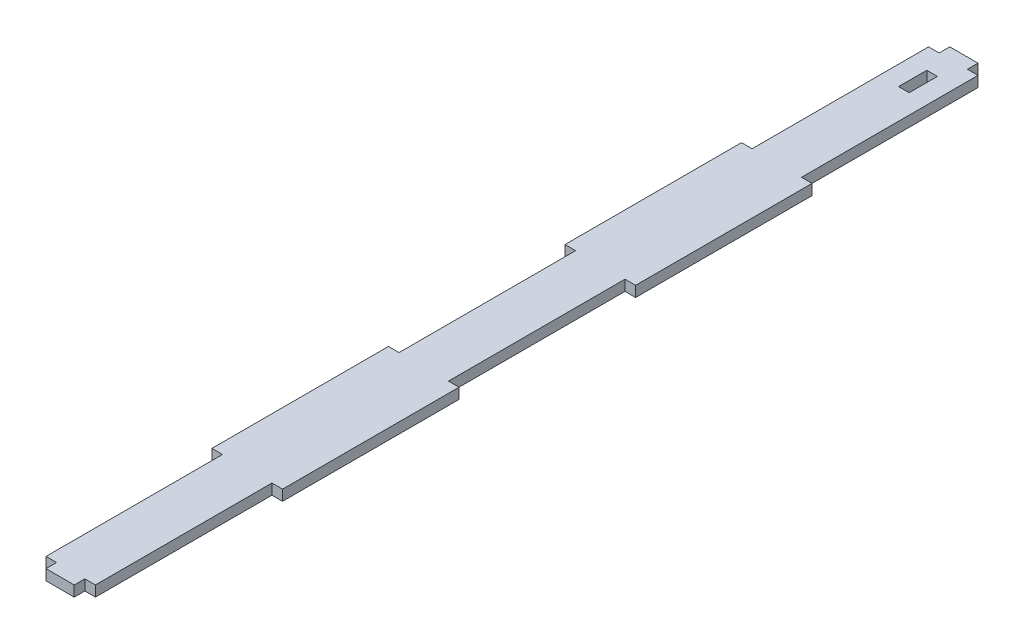
SolidWorks part; units mm, degrees
ref_plane "Alzado" through (0, 0, 0) normal (0, 0, 1) x (1, 0, 0)
ref_plane "Planta" through (0, 0, 0) normal (0, 1, 0) x (1, 0, 0)
ref_plane "Vista lateral" through (0, 0, 0) normal (1, 0, 0) x (0, 0, -1)
sketch "Croquis1" plane through (0, 0, 0) normal (0, 1, 0) x (1, 0, 0)
  line L0 (10, 253.1162) -> (14, 253.1162)
  line L1 (20, 50.1162) -> (20, 100.1162)
  line L2 (3, 200.1162) -> (0, 200.1162)
  line L3 (17, 250.1162) -> (17, 200.1162)
  line L4 (3, 100.1162) -> (3, 150.1162)
  line L5 (20, 150.1162) -> (17, 150.1162)
  line L6 (20, 150.1162) -> (20, 200.1162)
  line L7 (17, 200.1162) -> (20, 200.1162)
  line L8 (0, 200.1162) -> (0, 150.1162)
  line L9 (0, 100.1162) -> (0, 50.1162)
  line L10 (17, 250.1162) -> (14, 250.1162)
  line L12 (17, 150.1162) -> (17, 100.1162)
  line L13 (3, 150.1162) -> (3, 100.1162)
  line L14 (17, 50.1162) -> (20, 50.1162)
  line L15 (10, 253.1162) -> (10, 240.1162) construction
  line L16 (20, 100.1162) -> (17, 100.1162)
  line L17 (3, 100.1162) -> (0, 100.1162)
  line L18 (17, 50.1162) -> (17, 0.1162)
  line L19 (0, 150.1162) -> (3, 150.1162)
  line L20 (0, 100.1162) -> (3, 100.1162)
  line L22 (10, 253.1162) -> (6, 253.1162)
  line L23 (3, 50.1162) -> (0, 50.1162)
  line L24 (6, 253.1162) -> (6, 250.1162)
  line L27 (14, 253.1162) -> (14, 250.1162)
  line L28 (0, 100.1162) -> (0, 50.1162)
  line L30 (6, 250.1162) -> (3, 250.1162)
  line L31 (17, 0.1162) -> (14, 0.1162)
  line L33 (14, -2.8838) -> (6, -2.8838)
  line L34 (6, -2.8838) -> (6, 0.1162)
  line L35 (14, -2.8838) -> (14, 0.1162)
  line L36 (6, 0.1162) -> (3, 0.1162)
  line L43 (3, 0.1162) -> (3, 50.1162)
  line L44 (3, 200.1162) -> (3, 250.1162)
  line L45 (10, 240.1162) -> (10, 244.1162)
  line L46 (10, 244.1162) -> (8.5, 244.1162)
  line L47 (8.5, 244.1162) -> (8.5, 236.1162)
  line L48 (8.5, 236.1162) -> (11.5, 236.1162)
  line L49 (11.5, 236.1162) -> (11.5, 244.1162)
  line L50 (11.5, 244.1162) -> (10, 244.1162)
  dimension "D2" = 50
  dimension "D3" = 50
  dimension "D4" = 13
  dimension "D5" = 3
  dimension "D6" = 50
  dimension "D7" = 50
  dimension "D8" = 3
  dimension "D9" = 4
  dimension "D10" = 1.5
  dimension "D11" = 8
  dimension "D12" = 3
  dimension "D13" = 50
  dimension "D14" = 50
  dimension "D15" = 50
  dimension "D16" = 50
  dimension "D17" = 50
  dimension "D18" = 50
extrude "Saliente-Extruir1" add sketch "Croquis1" along normal blind 3
